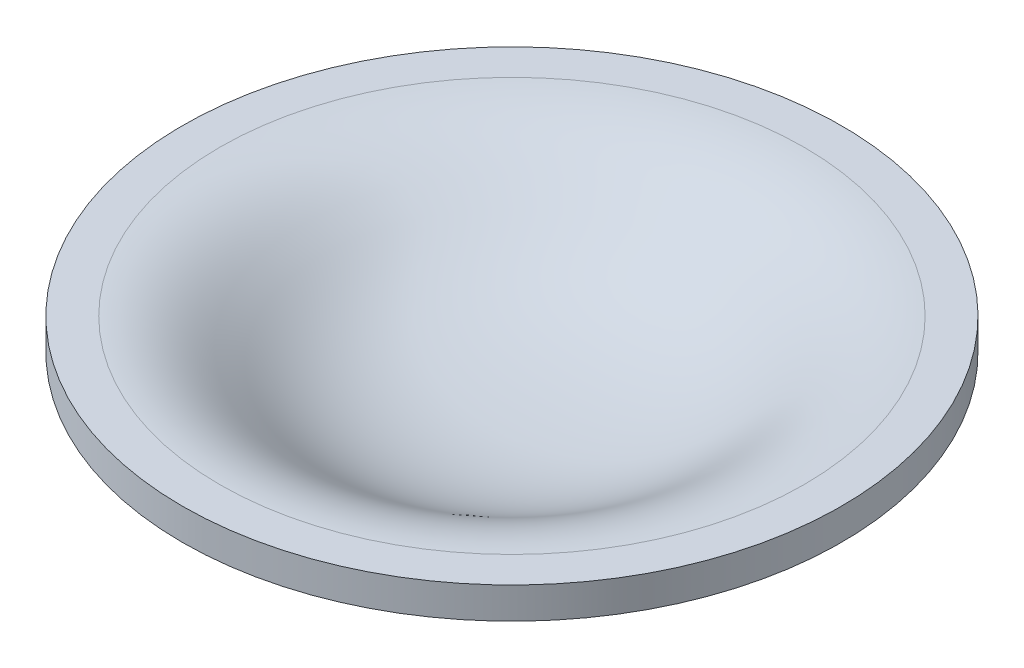
SolidWorks part; units mm, degrees
material "POLYURETHANE (11671)"
ref_plane "Plan de face" through (0, 0, 0) normal (0, 0, 1) x (1, 0, 0)
ref_plane "Plan de dessus" through (0, 0, 0) normal (0, 1, 0) x (1, 0, 0)
ref_plane "Plan de droite" through (0, 0, 0) normal (1, 0, 0) x (0, 0, -1)
sketch "Esquisse1" plane through (0, 0, 0) normal (0, 0, 1) x (1, 0, 0)
  line L0 (0, 0) -> (105, 0) construction
  line L1 (105, 0) -> (105, 30) construction
  line L2 (105, 30) -> (105, 40)
  line L3 (105, 40) -> (93.0884, 40)
  line L4 (105, 30) -> (93.0884, 30)
  line L5 (0, 0) -> (0, 10)
  line L6 (0, 0) -> (0, -31.6188) construction
  spline S0 degree 3 poles (0, 0) (63.671, 0) (65.8748, 30) (93.0884, 30) knots 0 0 0 0 1 1 1 1
  spline S1 degree 1 poles (0, 10) (93.0884, 40) knots 0 0 1 1 construction
  spline S2 degree 3 poles (0, 10) (0.9302, 10) (2.8129, 10.0139) (6.399, 10.0954) (10.675, 10.2938) (15.4532, 10.6739) (21.39, 11.3532) (28.0346, 12.4945) (34.9184, 14.2354) (40.8755, 16.2619) (47.8134, 19.2525) (55.0472, 23.3981) (62.7696, 28.758) (69.5016, 33.28) (75.7476, 36.4647) (80.9712, 38.4157) (85.7936, 39.4859) (89.8767, 39.9254) (92.0262, 40) (93.0884, 40) knots 0 0 0 0 0.015625 0.03125 0.0625 0.09375 0.125 0.1875 0.25 0.3125 0.375 0.5 0.625 0.75 0.8125 0.875 0.9375 0.96875 1 1 1 1
  dimension "D1" = 105
  dimension "D2" = 30
  dimension "D3" = 10
revolve "Révolution1" add sketch "Esquisse1" angle 360 about L6
